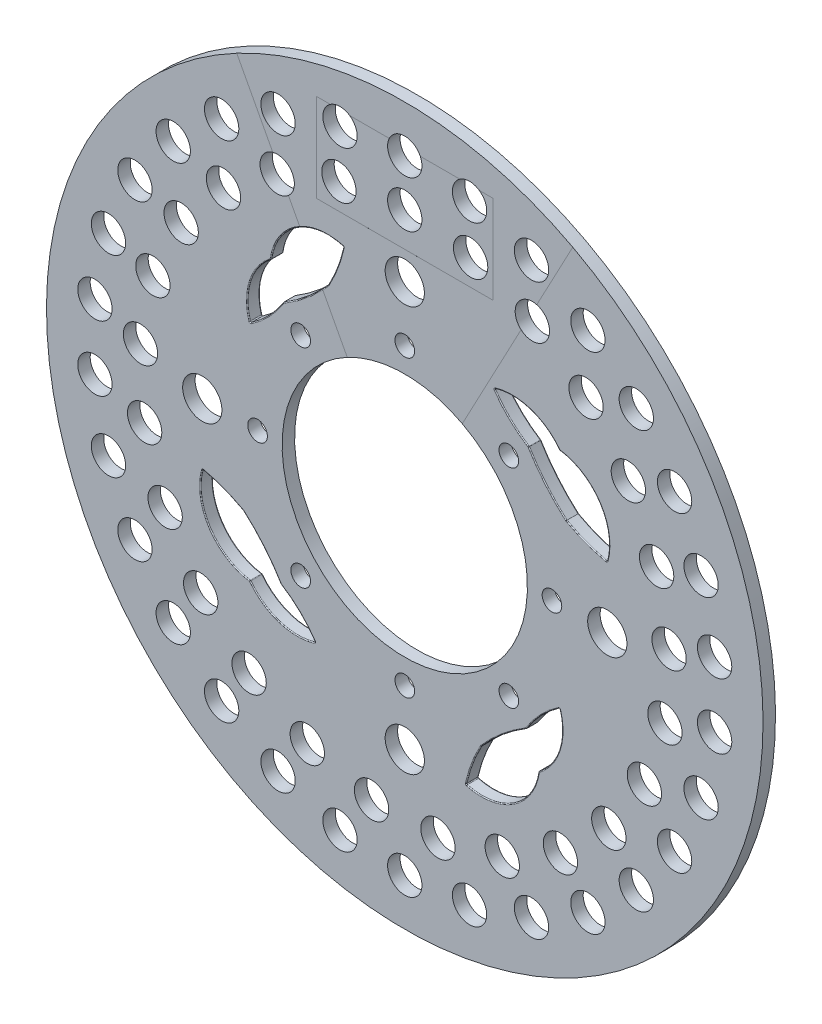
SolidWorks part; units mm, degrees
material "Plain Carbon Steel"
ref_plane "Front Plane" through (0, 0, 0) normal (0, 0, 1) x (1, 0, 0)
ref_plane "Top Plane" through (0, 0, 0) normal (0, 1, 0) x (1, 0, 0)
ref_plane "Right Plane" through (0, 0, 0) normal (1, 0, 0) x (0, 0, -1)
sketch "Sketch1" plane through (0, 0, 0) normal (0, 0, 1) x (1, 0, 0)
  line L0 (-36, 130) -> (-36, 94)
  line L1 (-36, 94) -> (36, 94)
  line L2 (36, 94) -> (36, 130)
  line L3 (36, 130) -> (-36, 130)
  line L4 (-68.4807, 129) -> (0, 0)
  line L5 (0, 0) -> (68.4807, 129)
  arc A0 (68.4807, 129) -> (-68.4807, 129) centre (0, 0) ccw
  point P7 (0, 130)
  dimension "D1" = 292.1
  dimension "D5" = 129
  dimension "D2" = 130
  dimension "D3" = 94
  dimension "D4" = 36
extrude "Boss-Extrude1" add sketch "Sketch1" along normal mid plane 5.0797
sketch "Sketch2" plane through (0, 0, 0) normal (0, 0, 1) x (1, 0, 0)
  line L1 (-36.4, 130) -> (36.4, 130)
  line L2 (-36.4, 130) -> (-36.4, 93.17)
  line L3 (-36.4, 93.17) -> (36.4, 93.17)
  line L4 (36.4, 130) -> (36.4, 93.17)
  dimension "D1" = 130
  dimension "D2" = 93.17
  dimension "D3" = 36.4
  dimension "D4" = 36.4
extrude "Boss-Extrude2" add sketch "Sketch2" along normal mid plane 5.0775
sketch "Sketch3" plane through (0, 0, 0) normal (0, 0, 1) x (1, 0, 0)
  line L0 (0, 0) -> (-68.4807, 129)
  line L1 (0, 0) -> (68.4807, 129)
  arc A0 (-68.4807, 129) -> (68.4807, 129) centre (0, 0) ccw
  dimension "D1" = 129
extrude "Boss-Extrude4" add sketch "Sketch3" along normal mid plane 5.08
sketch "Sketch4" plane through (0, 0, 0) normal (0, 0, 1) x (1, 0, 0)
  circle A0 centre (0, 0) radius 127 construction
  circle A1 centre (0, 127) radius 7
  circle A2 centre (26.4048, 124.2247) radius 7
  circle A3 centre (51.6556, 116.0203) radius 7
  circle A4 centre (74.6487, 102.7452) radius 7
  circle A5 centre (94.3794, 84.9796) radius 7
  circle A6 centre (109.9852, 63.5) radius 7
  circle A7 centre (120.7842, 39.2452) radius 7
  circle A8 centre (126.3043, 13.2751) radius 7
  circle A9 centre (126.3043, -13.2751) radius 7
  circle A10 centre (120.7842, -39.2452) radius 7
  circle A11 centre (109.9852, -63.5) radius 7
  circle A12 centre (94.3794, -84.9796) radius 7
  circle A13 centre (74.6487, -102.7452) radius 7
  circle A14 centre (51.6556, -116.0203) radius 7
  circle A15 centre (26.4048, -124.2247) radius 7
  circle A16 centre (0, -127) radius 7
  circle A17 centre (-26.4048, -124.2247) radius 7
  circle A18 centre (-51.6556, -116.0203) radius 7
  circle A19 centre (-74.6487, -102.7452) radius 7
  circle A20 centre (-94.3794, -84.9796) radius 7
  circle A21 centre (-109.9852, -63.5) radius 7
  circle A22 centre (-120.7842, -39.2452) radius 7
  circle A23 centre (-126.3043, -13.2751) radius 7
  circle A24 centre (-126.3043, 13.2751) radius 7
  circle A25 centre (-120.7842, 39.2452) radius 7
  circle A26 centre (-109.9852, 63.5) radius 7
  circle A27 centre (-94.3794, 84.9796) radius 7
  circle A28 centre (-74.6487, 102.7452) radius 7
  circle A29 centre (-51.6556, 116.0203) radius 7
  circle A30 centre (-26.4048, 124.2247) radius 7
  point P66 (0, 0)
  dimension "D1" = 254
  dimension "D2" = 14
  dimension "D3" = 30
extrude "Cut-Extrude1" cut sketch "Sketch4" against normal through all both and the other way through all
sketch "Sketch5" plane through (0, 0, 0) normal (0, 0, 1) x (1, 0, 0)
  circle A0 centre (0, 0) radius 107.95 construction
  circle A1 centre (0, 107.95) radius 7
  circle A2 centre (26.8461, 104.5586) radius 7
  circle A3 centre (52.0053, 94.5973) radius 7
  circle A4 centre (73.8969, 78.6922) radius 7
  circle A5 centre (91.1452, 57.8425) radius 7
  circle A6 centre (102.6666, 33.3584) radius 7
  circle A7 centre (107.737, 6.7782) radius 7
  circle A8 centre (106.0379, -20.2278) radius 7
  circle A9 centre (97.6761, -45.9629) radius 7
  circle A10 centre (83.1769, -68.8099) radius 7
  circle A11 centre (63.4514, -87.3334) radius 7
  circle A12 centre (39.739, -100.3694) radius 7
  circle A13 centre (13.5297, -107.0988) radius 7
  circle A14 centre (-13.5297, -107.0988) radius 7
  circle A15 centre (-39.739, -100.3694) radius 7
  circle A16 centre (-63.4514, -87.3334) radius 7
  circle A17 centre (-83.1769, -68.8099) radius 7
  circle A18 centre (-97.6761, -45.9629) radius 7
  circle A19 centre (-106.0379, -20.2278) radius 7
  circle A20 centre (-107.737, 6.7782) radius 7
  circle A21 centre (-102.6666, 33.3584) radius 7
  circle A22 centre (-91.1452, 57.8425) radius 7
  circle A23 centre (-73.8969, 78.6922) radius 7
  circle A24 centre (-52.0053, 94.5973) radius 7
  circle A25 centre (-26.8461, 104.5586) radius 7
  point P66 (0, 0)
  dimension "D1" = 215.9
  dimension "D2" = 14
  dimension "D3" = 25
extrude "Cut-Extrude2" cut sketch "Sketch5" against normal through all both and the other way through all
sketch "Sketch6" plane through (0, 0, 0) normal (0, 0, 1) x (1, 0, 0)
  circle A0 centre (0, 0) radius 82.55 construction
  circle A1 centre (-82.55, 0) radius 8
  circle A2 centre (0, 82.55) radius 8
  circle A3 centre (82.55, 0) radius 8
  circle A4 centre (0, -82.55) radius 8
  point P26 (0, 0)
  dimension "D1" = 165.1
  dimension "D2" = 16
  dimension "D3" = 4
extrude "Cut-Extrude3" cut sketch "Sketch6" against normal through all both and the other way through all
sketch "Sketch7" plane through (0, 0, 0) normal (0, 0, 1) x (1, 0, 0)
  circle A0 centre (0, 0) radius 50
  dimension "D1" = 100
extrude "Cut-Extrude4" cut sketch "Sketch7" against normal through all both and the other way through all
sketch "Sketch8" plane through (0, 0, 0) normal (0, 0, 1) x (1, 0, 0)
  circle A0 centre (0, 0) radius 60 construction
  circle A1 centre (0, 60) radius 4
  circle A2 centre (42.4264, 42.4264) radius 4
  circle A3 centre (60, 0) radius 4
  circle A4 centre (42.4264, -42.4264) radius 4
  circle A8 centre (0, -60) radius 4
  circle A9 centre (-42.4264, -42.4264) radius 4
  circle A10 centre (-60, 0) radius 4
  circle A11 centre (-42.4264, 42.4264) radius 4
  point P15 (0, 0)
  dimension "D1" = 120
  dimension "D2" = 8
  dimension "D3" = 8
extrude "Cut-Extrude5" cut sketch "Sketch8" against normal through all both and the other way through all
sketch "Sketch9" plane through (0, 0, 0) normal (0, 0, 1) x (1, 0, 0)
  circle A1 centre (0, 0) radius 72.8728 construction
  arc A26 (36.4811, 63.0838) -> (63.0838, 54.5544) centre (43.7541, 40.017) cw
  arc A27 (63.0838, 54.5544) -> (82.4321, 24.9434) centre (59.8299, 31.3015) cw
  arc A28 (65.8631, 31.1849) -> (82.4321, 24.9434) centre (95.7911, 85.5203) ccw
  arc A29 (65.8631, 31.1849) -> (50.5148, 49.5144) centre (117.1121, 89.6892) cw
  arc A30 (50.5148, 49.5144) -> (36.4811, 63.0838) centre (75.0466, 88.9272) cw
  arc A31 (31.1849, -65.8631) -> (24.9434, -82.4321) centre (85.5203, -95.7911) ccw
  arc A32 (54.5544, -63.0838) -> (24.9434, -82.4321) centre (31.3015, -59.8299) cw
  arc A33 (63.0838, -36.4811) -> (54.5544, -63.0838) centre (40.017, -43.7541) cw
  arc A34 (49.5144, -50.5148) -> (63.0838, -36.4811) centre (88.9272, -75.0466) cw
  arc A35 (31.1849, -65.8631) -> (49.5144, -50.5148) centre (89.6892, -117.1121) cw
  arc A36 (-65.8631, -31.1849) -> (-82.4321, -24.9434) centre (-95.7911, -85.5203) ccw
  arc A37 (-63.0838, -54.5544) -> (-82.4321, -24.9434) centre (-59.8299, -31.3015) cw
  arc A38 (-36.4811, -63.0838) -> (-63.0838, -54.5544) centre (-43.7541, -40.017) cw
  arc A39 (-50.5148, -49.5144) -> (-36.4811, -63.0838) centre (-75.0466, -88.9272) cw
  arc A40 (-65.8631, -31.1849) -> (-50.5148, -49.5144) centre (-117.1121, -89.6892) cw
  arc A41 (-31.1849, 65.8631) -> (-24.9434, 82.4321) centre (-85.5203, 95.7911) ccw
  arc A42 (-54.5544, 63.0838) -> (-24.9434, 82.4321) centre (-31.3015, 59.8299) cw
  arc A43 (-63.0838, 36.4811) -> (-54.5544, 63.0838) centre (-40.017, 43.7541) cw
  arc A44 (-49.5144, 50.5148) -> (-63.0838, 36.4811) centre (-88.9272, 75.0466) cw
  arc A45 (-31.1849, 65.8631) -> (-49.5144, 50.5148) centre (-89.6892, 117.1121) cw
  point P40 (0, 0)
  point P47 (0, 0)
  point P61 (0, 0)
  dimension "D4" = 145.7455
  dimension "D1" = 4
extrude "Cut-Extrude6" cut sketch "Sketch9" against normal through all both and the other way through all
fillet "Fillet1" radius 0.35 68 edges at (73.9238, 27.47, 2.54) (73.9238, 27.47, -2.54) (57.4805, 39.7564, 2.54) (57.4805, 39.7564, -2.54) (65.8631, 31.1849, 0) (42.7767, 55.5531, 2.54) (42.7767, 55.5531, -2.54) (50.5148, 49.5144, 0) (51.1385, 63.0484, 2.54) (51.1385, 63.0484, -2.54) (36.4811, 63.0838, 0) (79.4854, 44.1447, 2.54) (82.4321, 24.9434, 0) (79.4854, 44.1447, -2.54) (63.0838, 54.5544, 0) (44.1447, -79.4854, 2.54) (44.1447, -79.4854, -2.54) (27.47, -73.9238, 2.54) (27.47, -73.9238, -2.54) (24.9434, -82.4321, 0) (39.7564, -57.4805, 2.54) (39.7564, -57.4805, -2.54) (31.1849, -65.8631, 0) (55.5531, -42.7767, 2.54) (55.5531, -42.7767, -2.54) (49.5144, -50.5148, 0) (63.0484, -51.1385, 2.54) (54.5544, -63.0838, 0) (63.0484, -51.1385, -2.54) (63.0838, -36.4811, 0) (-79.4854, -44.1447, 2.54) (-79.4854, -44.1447, -2.54) (-73.9238, -27.47, 2.54) (-73.9238, -27.47, -2.54) (-82.4321, -24.9434, 0) (-57.4805, -39.7564, 2.54) (-57.4805, -39.7564, -2.54) (-65.8631, -31.1849, 0) (-42.7767, -55.5531, 2.54) (-42.7767, -55.5531, -2.54) (-50.5148, -49.5144, 0) (-51.1385, -63.0484, 2.54) (-63.0838, -54.5544, 0) (-51.1385, -63.0484, -2.54) (-36.4811, -63.0838, 0) (-27.47, 73.9238, -2.5399) (-27.47, 73.9238, 2.5399) (-42.6676, 80.3749, 2.5399) (-34.0086, 83.1528, 2.5399) (-24.9434, 82.4321, 0) (-34.0086, 83.1528, -2.5399) (-42.6676, 80.3749, -2.5399) (-50.65, 73.131, -2.54) (-50.65, 73.131, 2.54) (-33.5784, 63.2531, 2.5399) (-41.1269, 56.3591, 2.54) (-41.1269, 56.3591, -2.54) (-33.5784, 63.2531, -2.5399) (-32.3668, 64.5444, -2.5399) (-31.1849, 65.8631, 0) (-32.3668, 64.5444, 2.5399) (-55.5531, 42.7767, 2.54) (-55.5531, 42.7767, -2.54) (-49.5144, 50.5148, 0) (-63.0484, 51.1385, 2.54) (-54.5544, 63.0838, 0) (-63.0484, 51.1385, -2.54) (-63.0838, 36.4811, 0)
